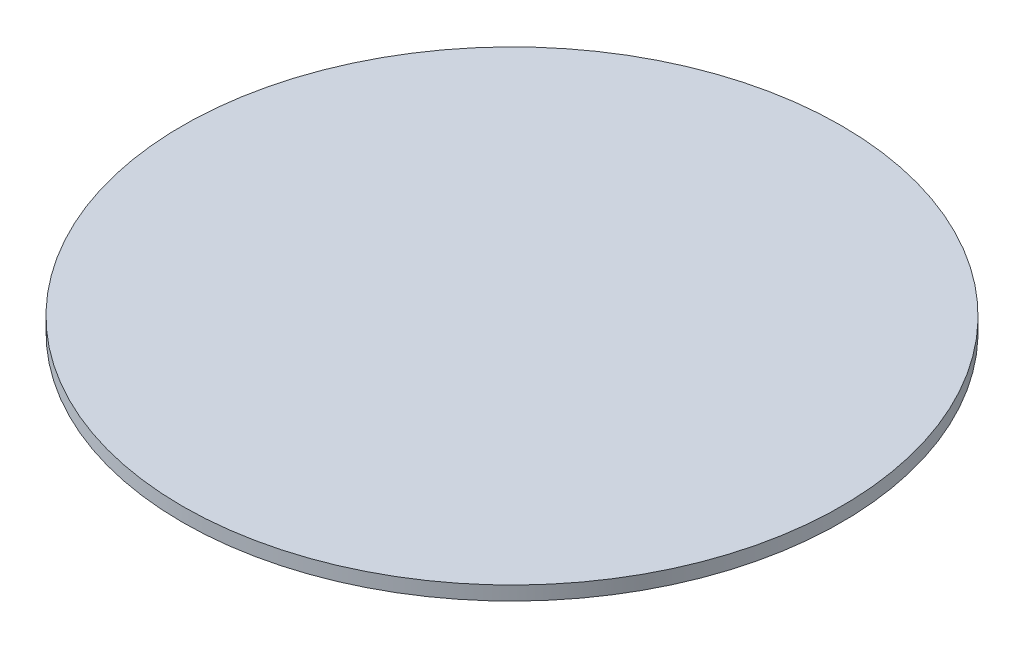
SolidWorks part; units mm, degrees
ref_plane "Front Plane" through (0, 0, 0) normal (0, 0, 1) x (1, 0, 0)
ref_plane "Top Plane" through (0, 0, 0) normal (0, 1, 0) x (1, 0, 0)
ref_plane "Right Plane" through (0, 0, 0) normal (1, 0, 0) x (0, 0, -1)
sketch "Sketch1" plane through (0, 0, 0) normal (0, 1, 0) x (1, 0, 0)
  circle A0 centre (0, 0) radius 75.184
extrude "Boss-Extrude1" add sketch "Sketch1" along normal blind 3.175
